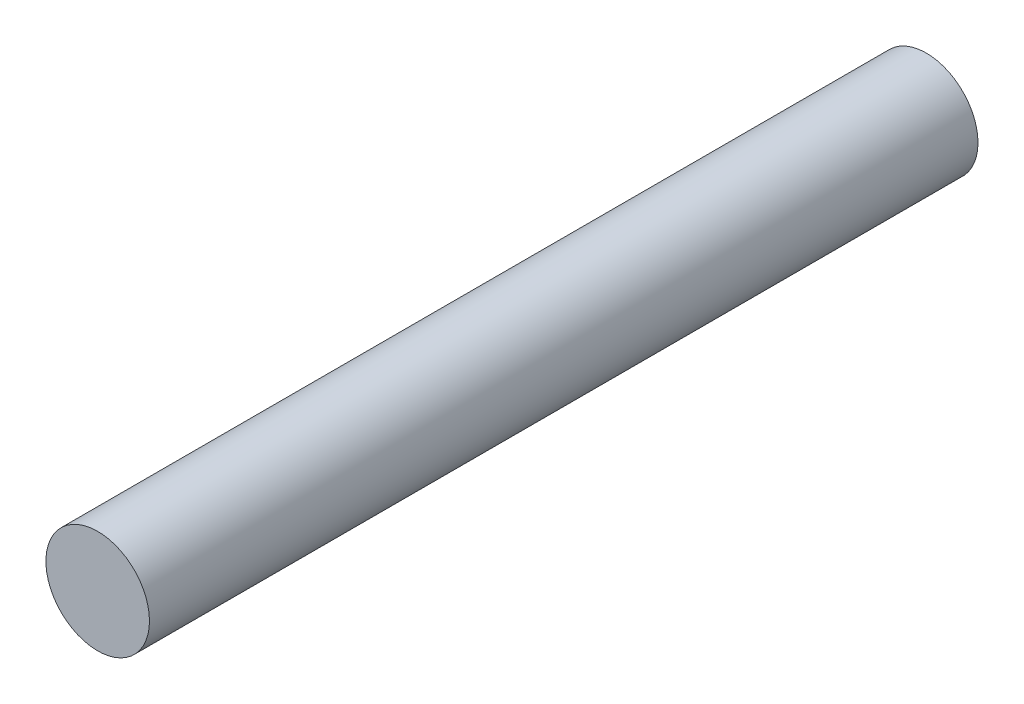
SolidWorks part; units mm, degrees
material "2024 Alloy"
ref_plane "Front Plane" through (0, 0, 0) normal (0, 0, 1) x (1, 0, 0)
ref_plane "Top Plane" through (0, 0, 0) normal (0, 1, 0) x (1, 0, 0)
ref_plane "Right Plane" through (0, 0, 0) normal (1, 0, 0) x (0, 0, -1)
sketch "Sketch1" plane through (0, 0, 0) normal (0, 0, 1) x (1, 0, 0)
  circle A0 centre (0, 0) radius 3.9688
extrude "Boss-Extrude1" add sketch "Sketch1" along normal mid plane 63.5
